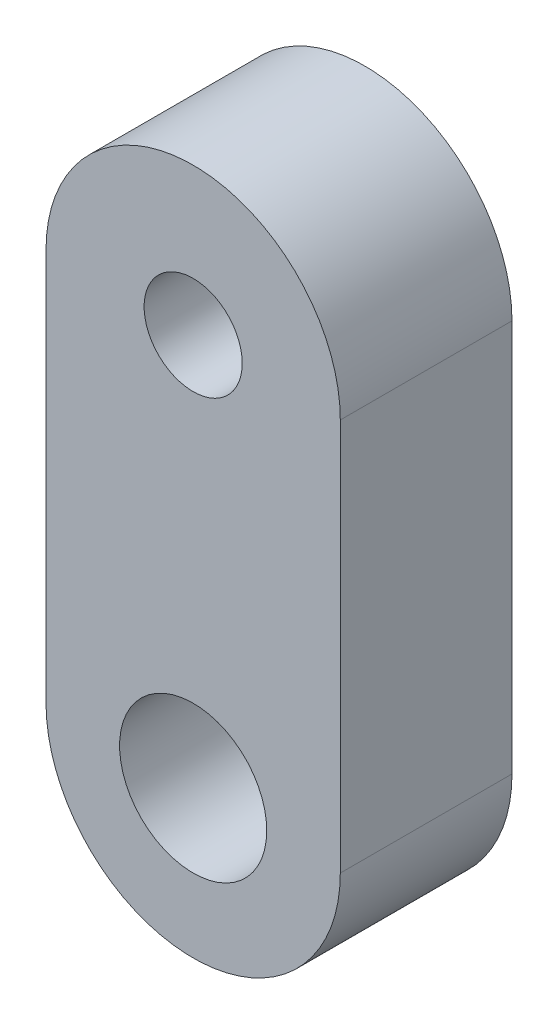
SolidWorks part; units mm, degrees
ref_plane "Front Plane" through (0, 0, 0) normal (0, 0, 1) x (1, 0, 0)
ref_plane "Top Plane" through (0, 0, 0) normal (0, 1, 0) x (1, 0, 0)
ref_plane "Right Plane" through (0, 0, 0) normal (1, 0, 0) x (0, 0, -1)
sketch "Sketch1" plane through (0, 0, 0) normal (0, 0, 1) x (1, 0, 0)
  line L0 (-3, 0) -> (-3, 8)
  line L1 (3, 0) -> (3, 8)
  arc A0 (-3, 0) -> (3, 0) centre (0, 0) ccw
  circle A1 centre (0, 0) radius 1.5
  arc A2 (3, 8) -> (-3, 8) centre (0, 8) ccw
  circle A3 centre (0, 8) radius 1
  dimension "D1" = 6
  dimension "D2" = 3
  dimension "D5" = 6
  dimension "D6" = 2
  dimension "D3" = 8
  dimension "D4" = 8
extrude "Boss-Extrude1" add sketch "Sketch1" along normal blind 3.5
